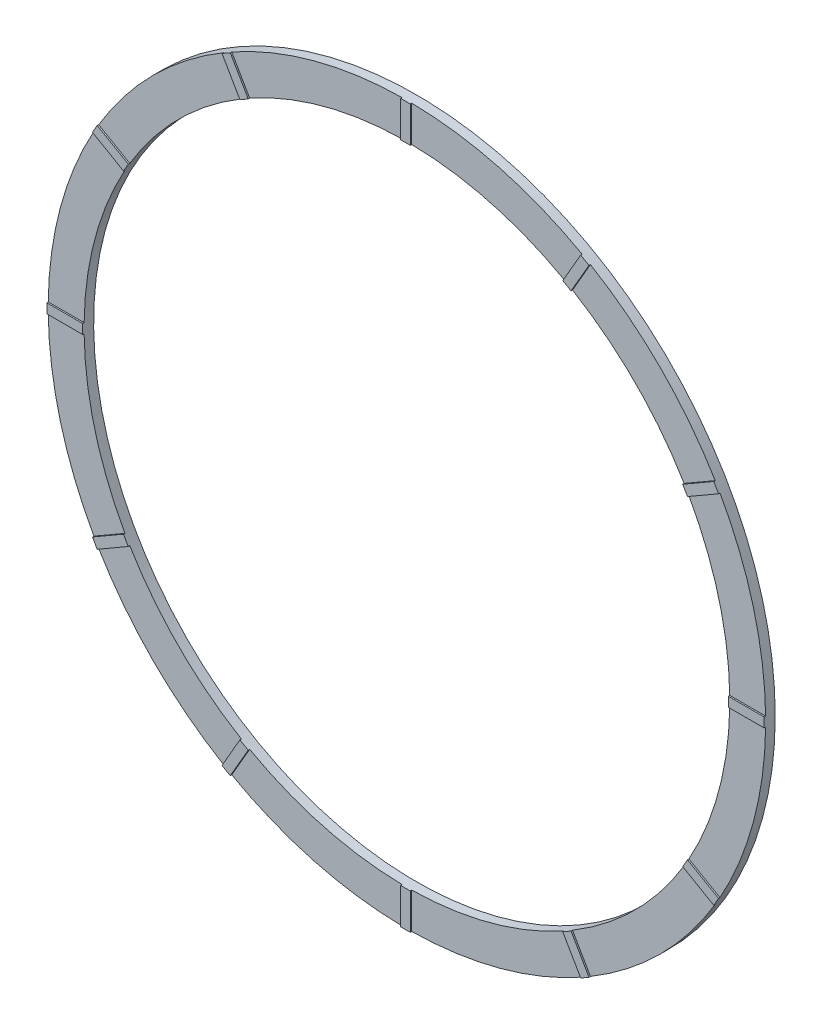
SolidWorks part; units mm, degrees
ref_plane "Front Plane" through (0, 0, 0) normal (0, 0, 1) x (1, 0, 0)
ref_plane "Top Plane" through (0, 0, 0) normal (0, 1, 0) x (1, 0, 0)
ref_plane "Right Plane" through (0, 0, 0) normal (1, 0, 0) x (0, 0, -1)
sketch "Sketch1" plane through (0, 0, 0) normal (0, 0, 1) x (1, 0, 0)
  circle A0 centre (0, 0) radius 7.5
  circle A1 centre (0, 0) radius 6.75
  dimension "D1" = 13.5
  dimension "D2" = 15
extrude "Boss-Extrude1" add sketch "Sketch1" along normal blind 0.2 contours A0 A1
sketch "Sketch2" plane through (0, 0, 0.2) normal (0, 0, 1) x (1, 0, 0)
  line L0 (0, 0) -> (0, 4.5084) construction
  line L1 (3.6631, 6.5446) -> (3.288, 5.895)
  line L2 (3.8363, 6.4446) -> (3.4612, 5.795)
  line L3 (-0.1, 7.4993) -> (-0.1, 6.7493)
  line L4 (6.4446, 3.8363) -> (5.795, 3.4612)
  line L5 (0.1, 7.4993) -> (0.1, 6.7493)
  line L6 (6.5446, 3.6631) -> (5.895, 3.288)
  line L7 (7.4993, 0.1) -> (6.7493, 0.1)
  line L8 (7.4993, -0.1) -> (6.7493, -0.1)
  line L9 (6.5446, -3.6631) -> (5.895, -3.288)
  line L10 (6.4446, -3.8363) -> (5.795, -3.4612)
  line L11 (3.8363, -6.4446) -> (3.4612, -5.795)
  line L12 (3.6631, -6.5446) -> (3.288, -5.895)
  line L13 (0.1, -7.4993) -> (0.1, -6.7493)
  line L14 (-0.1, -7.4993) -> (-0.1, -6.7493)
  line L15 (-3.6631, -6.5446) -> (-3.288, -5.895)
  line L16 (-3.8363, -6.4446) -> (-3.4612, -5.795)
  line L17 (-6.4446, -3.8363) -> (-5.795, -3.4612)
  line L18 (-6.5446, -3.6631) -> (-5.895, -3.288)
  line L19 (-7.4993, -0.1) -> (-6.7493, -0.1)
  line L20 (-7.4993, 0.1) -> (-6.7493, 0.1)
  line L21 (-6.5446, 3.6631) -> (-5.895, 3.288)
  line L22 (-6.4446, 3.8363) -> (-5.795, 3.4612)
  line L23 (-3.8363, 6.4446) -> (-3.4612, 5.795)
  line L24 (-3.6631, 6.5446) -> (-3.288, 5.895)
  arc A0 (-3.288, 5.895) -> (-3.4612, 5.795) centre (0, 0) ccw
  arc A1 (-3.6631, 6.5446) -> (-3.8363, 6.4446) centre (0, 0) ccw
  arc A2 (0.1, 7.4993) -> (-0.1, 7.4993) centre (0, 0) ccw
  arc A3 (0.1, 6.7493) -> (-0.1, 6.7493) centre (0, 0) ccw
  arc A4 (-5.795, 3.4612) -> (-5.895, 3.288) centre (0, 0) ccw
  arc A5 (-6.4446, 3.8363) -> (-6.5446, 3.6631) centre (0, 0) ccw
  arc A6 (-6.7493, 0.1) -> (-6.7493, -0.1) centre (0, 0) ccw
  arc A7 (-7.4993, 0.1) -> (-7.4993, -0.1) centre (0, 0) ccw
  arc A8 (-6.5446, -3.6631) -> (-6.4446, -3.8363) centre (0, 0) ccw
  arc A9 (-5.895, -3.288) -> (-5.795, -3.4612) centre (0, 0) ccw
  arc A10 (3.4612, 5.795) -> (3.288, 5.895) centre (0, 0) ccw
  arc A11 (3.8363, 6.4446) -> (3.6631, 6.5446) centre (0, 0) ccw
  arc A12 (5.895, 3.288) -> (5.795, 3.4612) centre (0, 0) ccw
  arc A13 (6.5446, 3.6631) -> (6.4446, 3.8363) centre (0, 0) ccw
  arc A14 (6.7493, -0.1) -> (6.7493, 0.1) centre (0, 0) ccw
  arc A15 (7.4993, -0.1) -> (7.4993, 0.1) centre (0, 0) ccw
  arc A16 (5.795, -3.4612) -> (5.895, -3.288) centre (0, 0) ccw
  arc A17 (6.4446, -3.8363) -> (6.5446, -3.6631) centre (0, 0) ccw
  arc A18 (3.288, -5.895) -> (3.4612, -5.795) centre (0, 0) ccw
  arc A19 (3.6631, -6.5446) -> (3.8363, -6.4446) centre (0, 0) ccw
  arc A20 (-0.1, -7.4993) -> (0.1, -7.4993) centre (0, 0) ccw
  arc A21 (-0.1, -6.7493) -> (0.1, -6.7493) centre (0, 0) ccw
  arc A22 (-3.4612, -5.795) -> (-3.288, -5.895) centre (0, 0) ccw
  arc A23 (-3.8363, -6.4446) -> (-3.6631, -6.5446) centre (0, 0) ccw
  point P55 (0, 0)
  dimension "D1" = 13.5
  dimension "D2" = 15
  dimension "D3" = 0.2
  dimension "D4" = 0.1
  dimension "D5" = 12
extrude "Boss-Extrude3" add sketch "Sketch2" along normal blind 0.03
